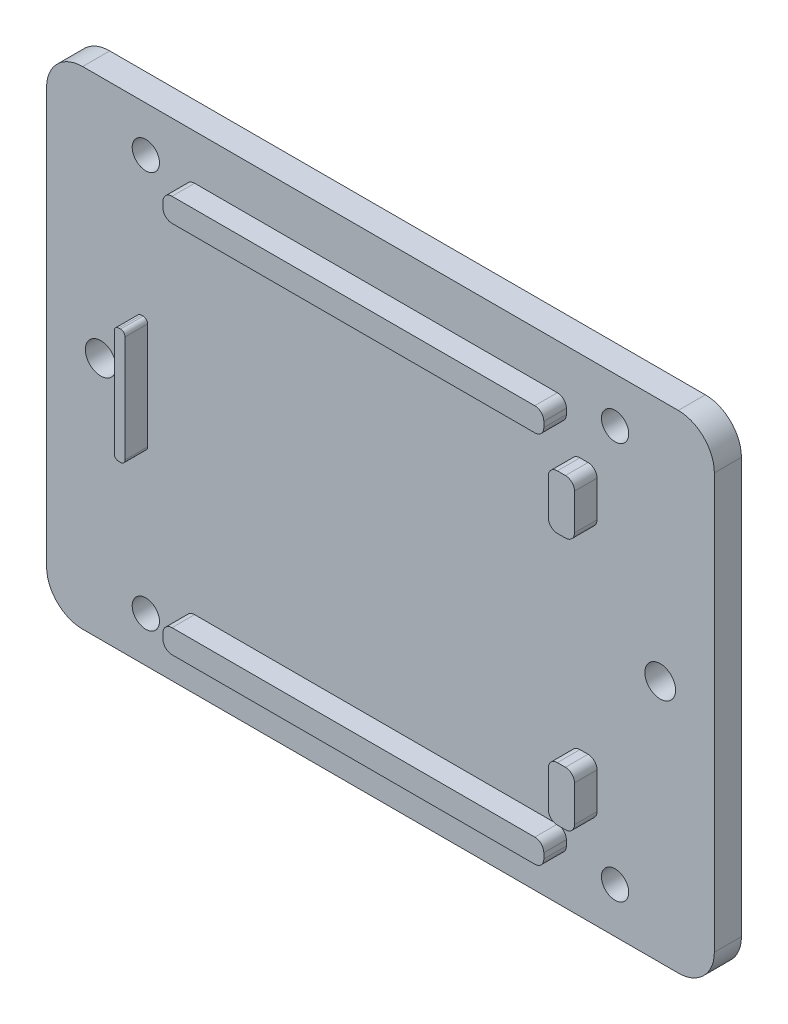
SolidWorks part; units mm, degrees
ref_plane "前视基准面" through (0, 0, 0) normal (0, 0, 1) x (1, 0, 0)
ref_plane "上视基准面" through (0, 0, 0) normal (0, 1, 0) x (1, 0, 0)
ref_plane "右视基准面" through (0, 0, 0) normal (1, 0, 0) x (0, 0, -1)
other "Configuration Table"
sketch "Outer_bed_74x54x3_Sketch" plane through (0, 0, 0) normal (0, 0, 1) x (1, 0, 0)
  line L0 (-33, -27) -> (33, -27)
  line L1 (37, -23) -> (37, 23)
  line L2 (33, 27) -> (-33, 27)
  line L3 (-37, 23) -> (-37, -23)
  arc A0 (33, -27) -> (37, -23) centre (33, -23) ccw
  arc A1 (37, 23) -> (33, 27) centre (33, 23) ccw
  arc A2 (-33, 27) -> (-37, 23) centre (-33, 23) ccw
  arc A3 (-37, -23) -> (-33, -27) centre (-33, -23) ccw
  circle A4 centre (-26, -22) radius 1.51
  circle A5 centre (-26, 22) radius 1.51
  circle A6 centre (26, -22) radius 1.51
  circle A7 centre (26, 22) radius 1.51
  circle A8 centre (-31, 0) radius 1.7
  circle A9 centre (31, 0) radius 1.7
extrude "Outer_bed_74x54x3" add sketch "Outer_bed_74x54x3_Sketch" along normal blind 3 separate body
sketch "Factory_case_locating_stops_Sketch" plane through (0, 0, 0) normal (0, 0, 1) x (1, 0, 0)
  line L0 (-20.6, -22) -> (19.6, -22)
  line L1 (20.6, -21) -> (20.6, -20.4)
  line L2 (19.6, -19.4) -> (-20.6, -19.4)
  line L3 (-21.6, -20.4) -> (-21.6, -21)
  line L4 (-20.6, 19.4) -> (19.6, 19.4)
  line L5 (20.6, 20.4) -> (20.6, 21)
  line L6 (19.6, 22) -> (-20.6, 22)
  line L7 (-21.6, 21) -> (-21.6, 20.4)
  line L8 (-26.5, -6.4) -> (-26.3, -6.4)
  line L9 (-25.8, -5.9) -> (-25.8, 5.9)
  line L10 (-26.3, 6.4) -> (-26.5, 6.4)
  line L11 (-27, 5.9) -> (-27, -5.9)
  line L12 (22.1, -17) -> (23, -17)
  line L13 (24, -16) -> (24, -12)
  line L14 (23, -11) -> (22.1, -11)
  line L15 (21.1, -12) -> (21.1, -16)
  line L16 (22.1, 11) -> (23, 11)
  line L17 (24, 12) -> (24, 16)
  line L18 (23, 17) -> (22.1, 17)
  line L19 (21.1, 16) -> (21.1, 12)
  arc A0 (19.6, -22) -> (20.6, -21) centre (19.6, -21) ccw
  arc A1 (20.6, -20.4) -> (19.6, -19.4) centre (19.6, -20.4) ccw
  arc A2 (-20.6, -19.4) -> (-21.6, -20.4) centre (-20.6, -20.4) ccw
  arc A3 (-21.6, -21) -> (-20.6, -22) centre (-20.6, -21) ccw
  arc A4 (19.6, 19.4) -> (20.6, 20.4) centre (19.6, 20.4) ccw
  arc A5 (20.6, 21) -> (19.6, 22) centre (19.6, 21) ccw
  arc A6 (-20.6, 22) -> (-21.6, 21) centre (-20.6, 21) ccw
  arc A7 (-21.6, 20.4) -> (-20.6, 19.4) centre (-20.6, 20.4) ccw
  arc A8 (-26.3, -6.4) -> (-25.8, -5.9) centre (-26.3, -5.9) ccw
  arc A9 (-25.8, 5.9) -> (-26.3, 6.4) centre (-26.3, 5.9) ccw
  arc A10 (-26.5, 6.4) -> (-27, 5.9) centre (-26.5, 5.9) ccw
  arc A11 (-27, -5.9) -> (-26.5, -6.4) centre (-26.5, -5.9) ccw
  arc A12 (23, -17) -> (24, -16) centre (23, -16) ccw
  arc A13 (24, -12) -> (23, -11) centre (23, -12) ccw
  arc A14 (22.1, -11) -> (21.1, -12) centre (22.1, -12) ccw
  arc A15 (21.1, -16) -> (22.1, -17) centre (22.1, -16) ccw
  arc A16 (23, 11) -> (24, 12) centre (23, 12) ccw
  arc A17 (24, 16) -> (23, 17) centre (23, 16) ccw
  arc A18 (22.1, 17) -> (21.1, 16) centre (22.1, 16) ccw
  arc A19 (21.1, 12) -> (22.1, 11) centre (22.1, 12) ccw
extrude "Factory_case_locating_stops" add sketch "Factory_case_locating_stops_Sketch" along normal blind 2.5 from offset 3
